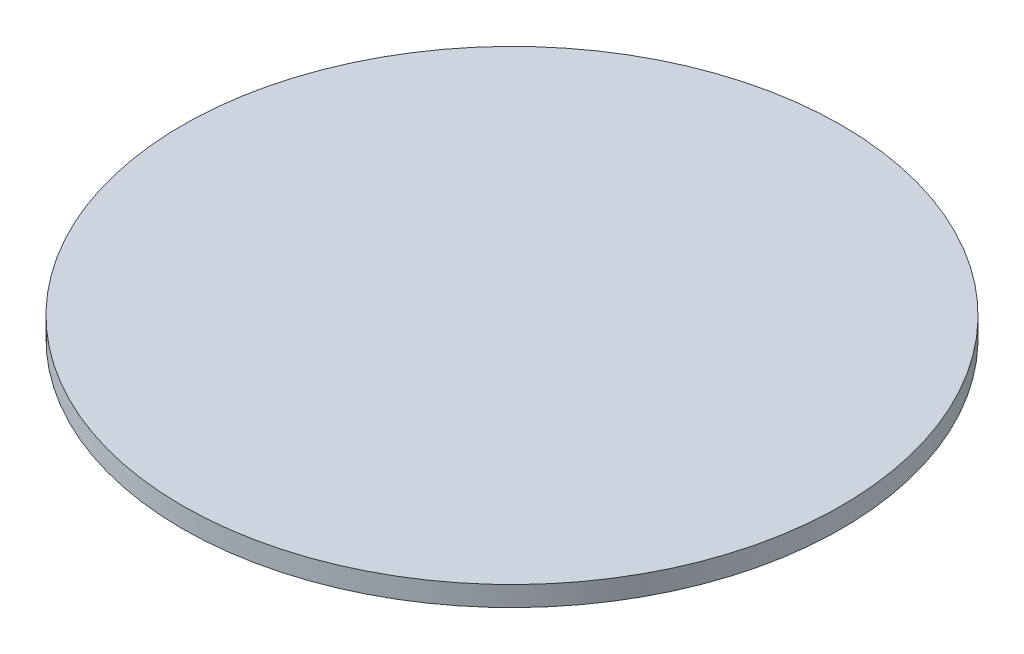
SolidWorks part; units mm, degrees
ref_plane "Front Plane" through (0, 0, 0) normal (0, 0, 1) x (1, 0, 0)
ref_plane "Top Plane" through (0, 0, 0) normal (0, 1, 0) x (1, 0, 0)
ref_plane "Right Plane" through (0, 0, 0) normal (1, 0, 0) x (0, 0, -1)
sketch "Sketch2" plane through (0, 0, 0) normal (0, 1, 0) x (1, 0, 0)
  circle A0 centre (0, 0) radius 69.85
  dimension "D1" = 139.7
extrude "Boss-Extrude1" add sketch "Sketch2" along normal blind 4.2333
